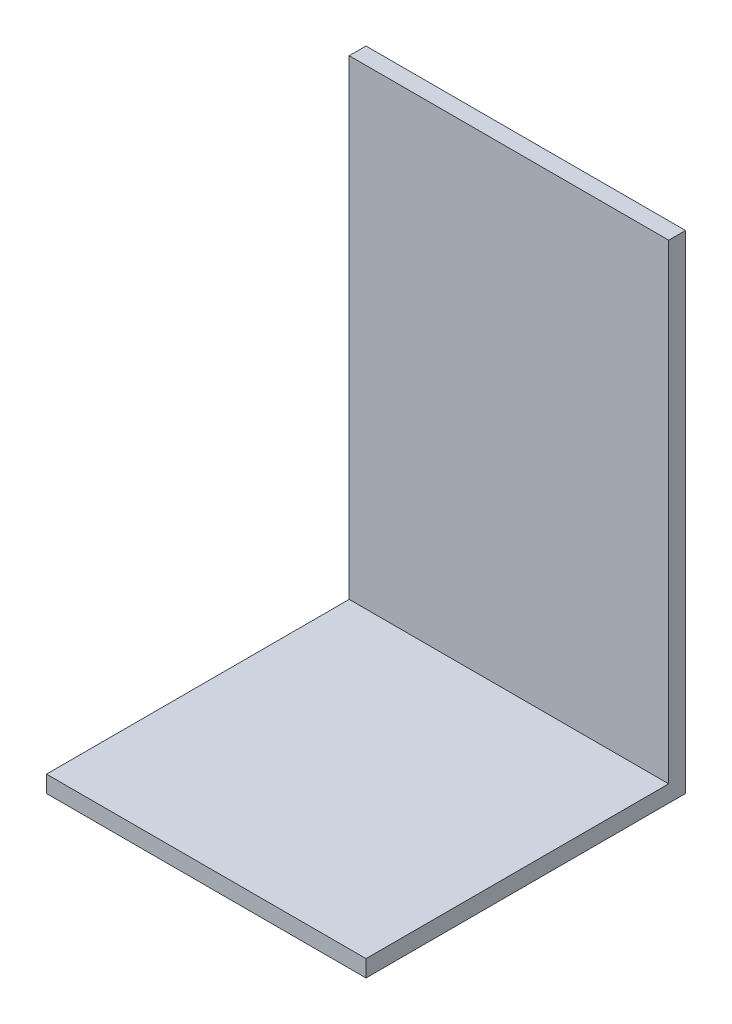
SolidWorks part; units mm, degrees
ref_plane "Front Plane" through (0, 0, 0) normal (0, 0, 1) x (1, 0, 0)
ref_plane "Top Plane" through (0, 0, 0) normal (0, 1, 0) x (1, 0, 0)
ref_plane "Right Plane" through (0, 0, 0) normal (1, 0, 0) x (0, 0, -1)
sketch "Sketch1" plane through (0, 0, 0) normal (0, 1, 0) x (1, 0, 0)
  line L1 (-32.0817, 34.7382) -> (5.9183, 34.7382)
  line L2 (-32.0817, 34.7382) -> (-32.0817, -3.2618)
  line L3 (-32.0817, -3.2618) -> (5.9183, -3.2618)
  line L4 (5.9183, 34.7382) -> (5.9183, -3.2618)
  dimension "D1" = 38
  dimension "D2" = 38
extrude "Boss-Extrude1" add sketch "Sketch1" along normal blind 2
sketch "Sketch2" plane through (0, 2, 0) normal (0, 1, 0) x (1, 0, 0)
  line L1 (-32.0817, 34.7382) -> (5.9183, 34.7382)
  line L2 (-32.0817, 34.7382) -> (-32.0817, 32.7382)
  line L3 (-32.0817, 32.7382) -> (5.9183, 32.7382)
  line L4 (5.9183, 34.7382) -> (5.9183, 32.7382)
  dimension "D1" = 2
  dimension "D2" = 38
extrude "Boss-Extrude2" add sketch "Sketch2" along normal blind 56
